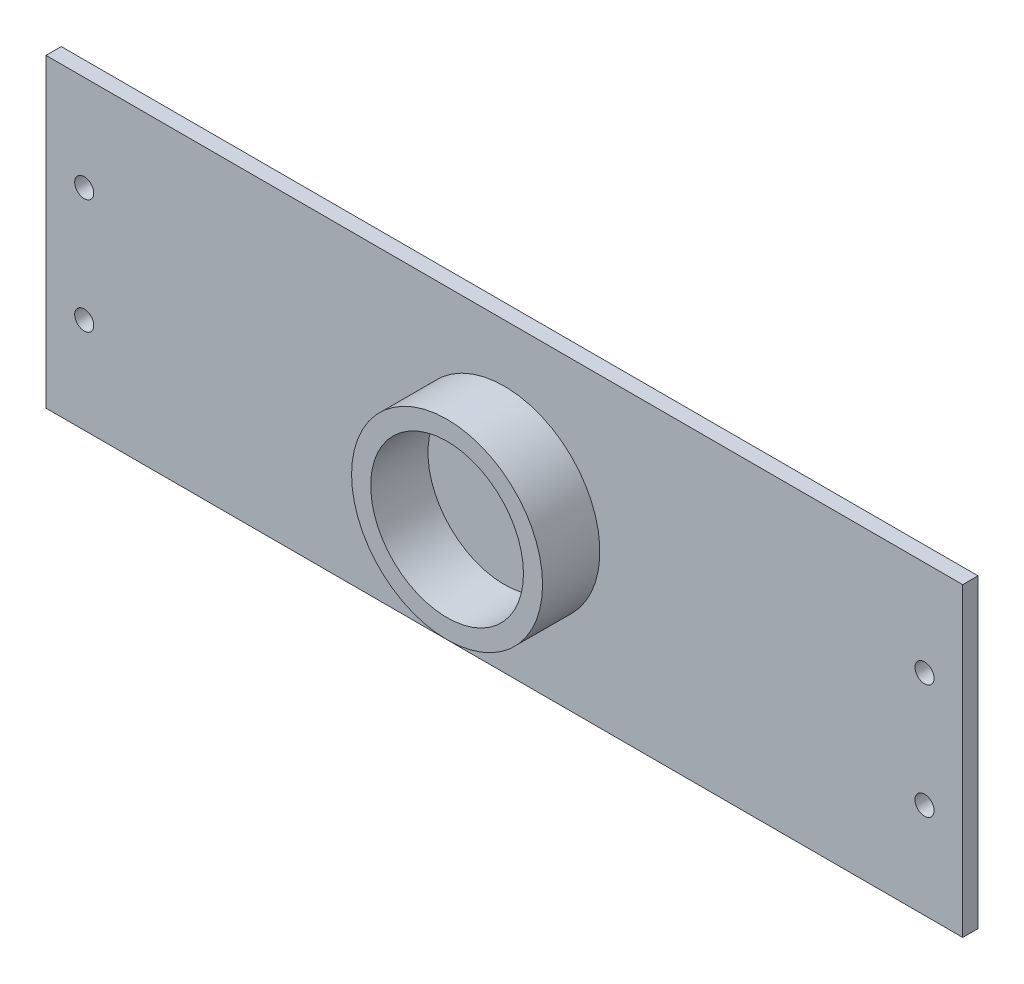
SolidWorks part; units mm, degrees
ref_plane "Plan de face" through (0, 0, 0) normal (0, 0, 1) x (1, 0, 0)
ref_plane "Plan de dessus" through (0, 0, 0) normal (0, 1, 0) x (1, 0, 0)
ref_plane "Plan de droite" through (0, 0, 0) normal (1, 0, 0) x (0, 0, -1)
sketch "Esquisse1" plane through (0, 0, 0) normal (0, 0, 1) x (1, 0, 0)
  line L0 (120, 55) -> (120, 25) construction
  line L1 (0, 0) -> (240, 0)
  line L2 (0, 0) -> (0, 80)
  line L3 (0, 80) -> (240, 80)
  line L4 (240, 0) -> (240, 80)
  line L5 (0, 0) -> (240, 80) construction
  line L6 (0, 80) -> (240, 0) construction
  circle A0 centre (10, 55) radius 2.5
  circle A1 centre (10, 25) radius 2.5
  circle A2 centre (230, 25) radius 2.5
  circle A3 centre (230, 55) radius 2.5
  point P4 (120, 40)
  dimension "D3" = 5
  dimension "D4" = 5
  dimension "D1" = 240
  dimension "D2" = 80
  dimension "D5" = 30
  dimension "D6" = 25
  dimension "D7" = 10
extrude "Boss.-Extru.1" add sketch "Esquisse1" along normal blind 4
sketch "Esquisse2" plane through (0, 0, 4) normal (0, 0, 1) x (1, 0, 0)
  circle A0 centre (120, 40) radius 25
  circle A1 centre (120, 40) radius 20
  dimension "D1" = 50
  dimension "D2" = 40
extrude "Boss.-Extru.2" add sketch "Esquisse2" along normal blind 15
